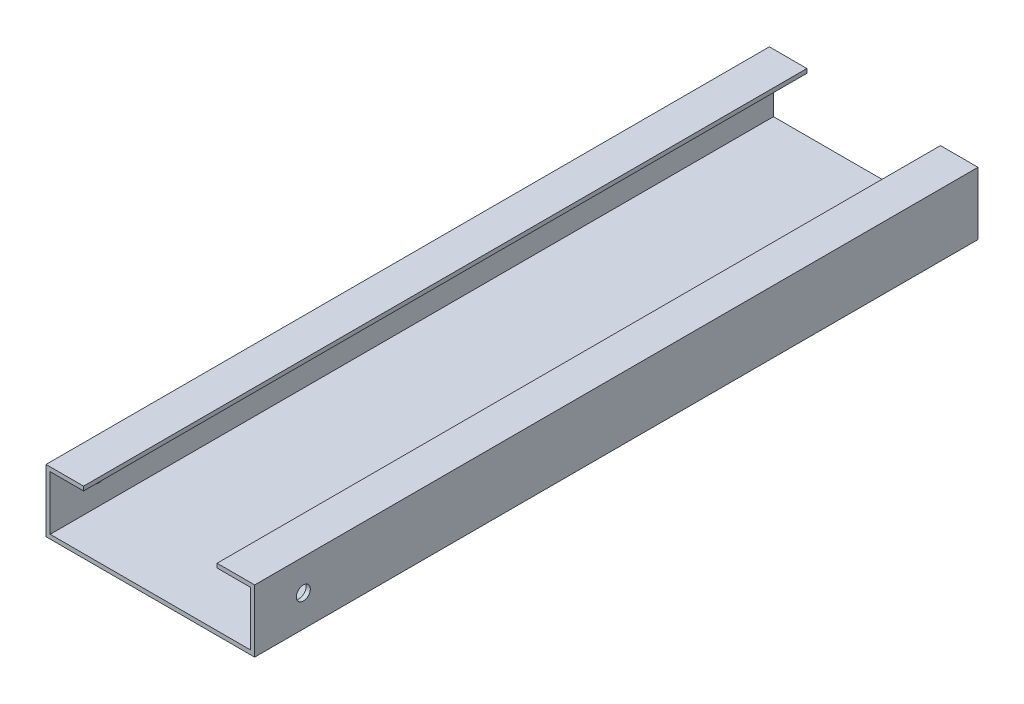
SolidWorks part; units mm, degrees
ref_plane "Front Plane" through (0, 0, 0) normal (0, 0, 1) x (1, 0, 0)
ref_plane "Top Plane" through (0, 0, 0) normal (0, 1, 0) x (1, 0, 0)
ref_plane "Right Plane" through (0, 0, 0) normal (1, 0, 0) x (0, 0, -1)
sketch "Sketch1" plane through (0, 0, 0) normal (0, 0, 1) x (1, 0, 0)
  line L1 (-75, 22.5) -> (75, 22.5)
  line L2 (-75, 22.5) -> (-75, -22.5)
  line L3 (-75, -22.5) -> (75, -22.5)
  line L4 (75, 22.5) -> (75, -22.5)
  line L5 (-75, 22.5) -> (75, -22.5) construction
  line L6 (-75, -22.5) -> (75, 22.5) construction
  point P0 (0, 0)
  dimension "D1" = 150
  dimension "D2" = 45
extrude "Boss-Extrude1" add sketch "Sketch1" along normal mid plane 520
sketch "Sketch2" plane through (0, 0, 0) normal (0, 0, 1) x (1, 0, 0)
  line L0 (-75, 22.5) -> (-75, -22.5) construction
  line L1 (-72, 19.5) -> (72, 19.5)
  line L2 (-72, 19.5) -> (-72, -19.5)
  line L3 (-72, -19.5) -> (72, -19.5)
  line L4 (72, 19.5) -> (72, -19.5)
  line L5 (-72, 19.5) -> (72, -19.5) construction
  line L6 (-72, -19.5) -> (72, 19.5) construction
  line L7 (-75, -22.5) -> (75, -22.5) construction
  point P0 (0, 0)
  dimension "D1" = 3
  dimension "D2" = 3
extrude "Cut-Extrude1" cut sketch "Sketch2" against normal through all both and the other way through all
sketch "Sketch3" plane through (0, 0, 260) normal (0, 0, 1) x (1, 0, 0)
  line L0 (75, 22.5) -> (-75, 22.5) construction
  line L1 (-48, 28.3789) -> (48, 28.3789)
  line L2 (-48, 28.3789) -> (-48, 16.6211)
  line L3 (-48, 16.6211) -> (48, 16.6211)
  line L4 (48, 28.3789) -> (48, 16.6211)
  line L5 (-48, 28.3789) -> (48, 16.6211) construction
  line L6 (-48, 16.6211) -> (48, 28.3789) construction
  line L7 (-72, 19.5) -> (-72, -19.5) construction
  point P0 (0, 22.5)
  dimension "D1" = 24
extrude "Cut-Extrude2" cut sketch "Sketch3" against normal through all
sketch "Sketch4" plane through (-75, 0, 0) normal (-1, 0, 0) x (0, 0, 1)
  line L0 (-260, 0) -> (260, 0) construction
  line L1 (-260, 22.5) -> (-260, -22.5) construction
  line L2 (260, 22.5) -> (260, -22.5) construction
  circle A0 centre (225, 0) radius 5
  dimension "D1" = 10
  dimension "D2" = 35
extrude "Cut-Extrude3" cut sketch "Sketch4" against normal through all contours A0
sketch "Sketch5" plane through (-75, 0, 0) normal (-1, 0, 0) x (0, 0, 1)
  line L0 (-260, 0) -> (260, 0) construction
  line L1 (-260, 22.5) -> (-260, -22.5) construction
  line L2 (260, 22.5) -> (260, -22.5) construction
